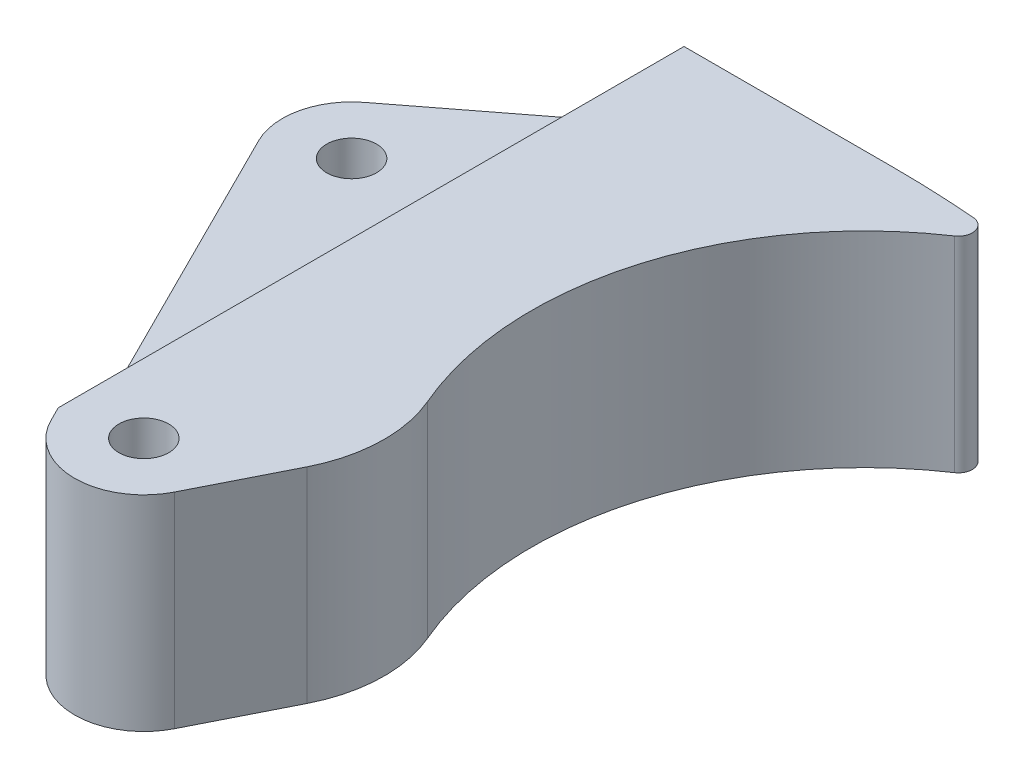
SolidWorks part; units mm, degrees
ref_plane "Front Plane" through (0, 0, 0) normal (0, 0, 1) x (1, 0, 0)
ref_plane "Top Plane" through (0, 0, 0) normal (0, 1, 0) x (1, 0, 0)
ref_plane "Right Plane" through (0, 0, 0) normal (1, 0, 0) x (0, 0, -1)
sketch "Sketch1" plane through (0, 0, 0) normal (0, 1, 0) x (1, 0, 0)
  line L1 (-5.6796, -2.8398) -> (-24.7296, 35.2602)
  line L3 (5.6707, -2.8576) -> (12.7, 11.0915)
  line L4 (-6.35, 55.88) -> (12.7, 55.88)
  line L5 (-22.9215, 43.1332) -> (-6.35, 55.88)
  circle A0 centre (0, 0) radius 2.286
  circle A1 centre (-19.05, 38.1) radius 2.286
  arc A2 (-5.6796, -2.8398) -> (5.6707, -2.8576) centre (0, 0) ccw
  arc A3 (-22.9215, 43.1332) -> (-24.7296, 35.2602) centre (-19.05, 38.1) ccw
  arc A4 (24.3886, 55.1618) -> (12.7, 55.88) centre (12.7, -39.599) ccw
  arc A5 (24.3886, 55.1618) -> (12.7, 11.0915) centre (38.1, 27.94) ccw
  dimension "D1" = 60.96
  dimension "D2" = 4.572
  dimension "D3" = 12.7
  dimension "D4" = 4.572
  dimension "D5" = 12.7
  dimension "D11" = 6.35
  dimension "D6" = 38.1
  dimension "D7" = 27.94
  dimension "D8" = 38.1
  dimension "D9" = 19.05
  dimension "D10" = 19.05
  dimension "D12" = 55.88
extrude "Boss-Extrude1" add sketch "Sketch1" along normal blind 76.2
sketch "Sketch2" plane through (0, 0, -55.88) normal (0, 0, -1) x (-1, 0, 0)
  line L1 (6.35, 0) -> (25.4, 0)
  line L2 (6.35, 0) -> (6.35, 63.5)
  line L3 (6.35, 63.5) -> (25.4, 63.5)
  line L4 (25.4, 0) -> (25.4, 63.5)
  line L5 (25.4, 0) -> (25.4, 76.2) construction
  line L7 (25.4, 76.2) -> (6.35, 76.2)
  line L8 (25.4, 76.2) -> (25.4, 69.85)
  line L9 (25.4, 69.85) -> (6.35, 69.85)
  line L10 (6.35, 76.2) -> (6.35, 69.85)
  line L12 (25.4, 76.2) -> (22.9215, 76.2) construction
  dimension "D2" = 6.35
  dimension "D3" = 6.35
extrude "Cut-Extrude1" cut sketch "Sketch2" against normal through all
sketch "Sketch3" plane through (-6.35, 0, 0) normal (-1, 0, 0) x (0, 0, 1)
  line L1 (6.35, 50.546) -> (-19.05, 50.546)
  line L2 (6.35, 50.546) -> (6.35, 57.404)
  line L3 (6.35, 57.404) -> (-19.05, 57.404)
  line L4 (-19.05, 50.546) -> (-19.05, 57.404)
  line L6 (6.35, 0) -> (6.35, 76.2) construction
  line L7 (1.499, 63.5) -> (-55.88, 63.5) construction
  line L8 (6.35, 0) -> (6.35, 76.2) construction
  dimension "D1" = 25.4
  dimension "D2" = 6.096
  dimension "D3" = 6.858
extrude "Cut-Extrude2" cut sketch "Sketch3" against normal through all
fillet "Fillet1" radius 1.27 1 edges at (24.3886, 38.1, -55.1618)
fillet "Fillet2" radius 12.7 2 edges at (12.7, 25.273, -11.0915) (12.7, 66.802, -11.0915)
sketch "Sketch4" plane through (0, 57.404, 0) normal (0, -1, 0) x (1, 0, 0)
  line L1 (-31.254, 11.4879) -> (27.7556, 11.4879)
  line L2 (-31.254, 11.4879) -> (-31.254, -62.8551)
  line L3 (-31.254, -62.8551) -> (27.7556, -62.8551)
  line L4 (27.7556, 11.4879) -> (27.7556, -62.8551)
extrude "Cut-Extrude3" cut sketch "Sketch4" along normal through all
